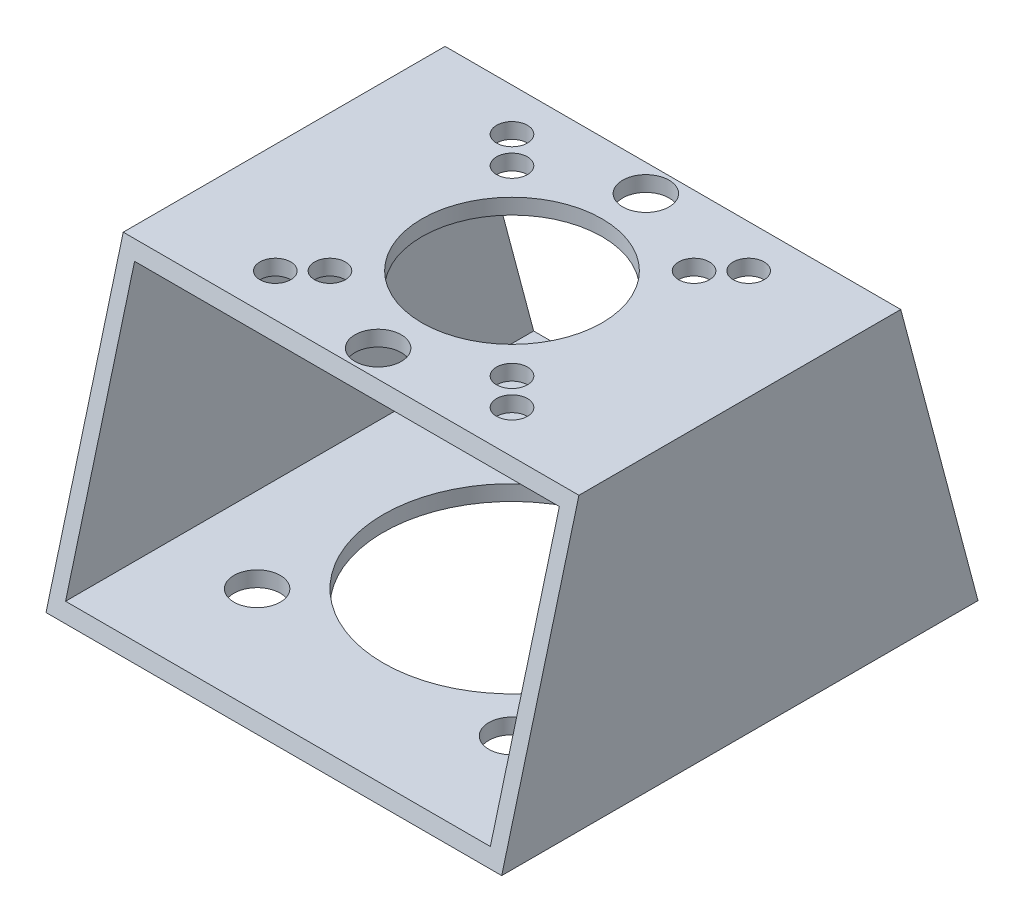
SolidWorks part; units mm, degrees
ref_plane "Front Plane" through (0, 0, 0) normal (0, 0, 1) x (1, 0, 0)
ref_plane "Top Plane" through (0, 0, 0) normal (0, 1, 0) x (1, 0, 0)
ref_plane "Right Plane" through (0, 0, 0) normal (1, 0, 0) x (0, 0, -1)
sketch "Sketch1" plane through (0, 0, 0) normal (0, 0, 1) x (1, 0, 0)
  line L1 (-82.5, -50.4745) -> (82.5, -50.4745)
  line L2 (-82.5, -50.4745) -> (-82.5, 50.4745)
  line L3 (-82.5, 50.4745) -> (82.5, 50.4745)
  line L4 (82.5, -50.4745) -> (82.5, 50.4745)
  line L5 (-82.5, -50.4745) -> (82.5, 50.4745) construction
  line L6 (-82.5, 50.4745) -> (82.5, -50.4745) construction
  point P0 (0, 0)
  dimension "D1" = 165
  dimension "D2" = 100.949
extrude "Extrude-Thin1" add sketch "Sketch1" along normal mid plane 185 thin
sketch "Sketch2" plane through (0, 56.4745, 0) normal (0, 1, 0) x (1, 0, 0)
  line L0 (0, 0) -> (-63.6444, -63.6444) construction
  line L1 (35.3553, -35.3553) -> (-35.3553, -35.3553) construction
  line L2 (35.3553, -35.3553) -> (35.3553, 35.3553) construction
  line L3 (35.3553, 35.3553) -> (-35.3553, 35.3553) construction
  line L4 (-35.3553, -35.3553) -> (-35.3553, 35.3553) construction
  line L5 (35.3553, -35.3553) -> (-35.3553, 35.3553) construction
  line L6 (35.3553, 35.3553) -> (-35.3553, -35.3553) construction
  circle A0 centre (0, 0) radius 35
  circle A1 centre (-35.3553, -35.3553) radius 6
  circle A2 centre (-45.9619, -45.9619) radius 6
  dimension "D1" = 70
  dimension "D2" = 12
  dimension "D3" = 50
  dimension "D4" = 65
extrude "Cut-Extrude1" cut sketch "Sketch2" against normal up to next
sketch "Sketch3" plane through (0, -56.4745, 0) normal (0, -1, 0) x (1, 0, 0)
  line L1 (49.4975, -49.4975) -> (-49.4975, -49.4975) construction
  line L2 (49.4975, -49.4975) -> (49.4975, 49.4975) construction
  line L3 (49.4975, 49.4975) -> (-49.4975, 49.4975) construction
  line L4 (-49.4975, -49.4975) -> (-49.4975, 49.4975) construction
  line L5 (49.4975, -49.4975) -> (-49.4975, 49.4975) construction
  line L6 (49.4975, 49.4975) -> (-49.4975, -49.4975) construction
  circle A0 centre (0, 0) radius 50
  circle A1 centre (-49.4975, -49.4975) radius 9
  point P8 (-63.9143, -63.9143)
  point P9 (-56.3553, -56.3553)
  dimension "D1" = 100
  dimension "D3" = 18
  dimension "D2" = 70
extrude "Cut-Extrude2" cut sketch "Sketch3" against normal blind 10
sketch "Sketch4" plane through (-88.5, 0, 0) normal (-1, 0, 0) x (0, 0, 1)
  line L0 (-92.5, -56.4745) -> (-62.5, 56.4745)
  line L1 (92.5, 56.4745) -> (-92.5, 56.4745) construction
  line L2 (-62.5, 56.4745) -> (-92.5, 56.4745)
  line L3 (-92.5, 56.4745) -> (-92.5, -56.4745)
  dimension "D1" = 30
extrude "Cut-Extrude3" cut sketch "Sketch4" against normal through all
mirror "Mirror1" about plane through (0, 0, 0) normal (0, 0, 1) of "Cut-Extrude3"
pattern_circular "CirPattern1" count 4 over 360 about axis through (0, 0, 0) along (0, 1, 0) of "Cut-Extrude2", "Cut-Extrude1"
sketch "Sketch5" plane through (0, 56.4745, 0) normal (0, 1, 0) x (1, 0, 0)
  circle A0 centre (0, -52) radius 9
  dimension "D2" = 18
  dimension "D1" = 52
extrude "Cut-Extrude4" cut sketch "Sketch5" against normal blind 10
mirror "Mirror2" about plane through (0, 0, 0) normal (0, 0, 1) of "Cut-Extrude4"
